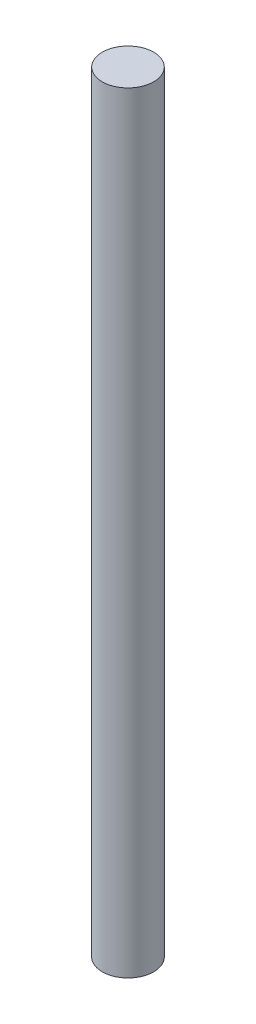
SolidWorks part; units mm, degrees
ref_plane "Спереди" through (0, 0, 0) normal (0, 0, 1) x (1, 0, 0)
ref_plane "Сверху" through (0, 0, 0) normal (0, 1, 0) x (1, 0, 0)
ref_plane "Справа" through (0, 0, 0) normal (1, 0, 0) x (0, 0, -1)
sketch "Эскиз1" plane through (0, 0, 0) normal (0, 1, 0) x (1, 0, 0)
  circle A0 centre (0, 0) radius 5
  dimension "D1" = 10
extrude "Бобышка-Вытянуть1" add sketch "Эскиз1" along normal blind 150
